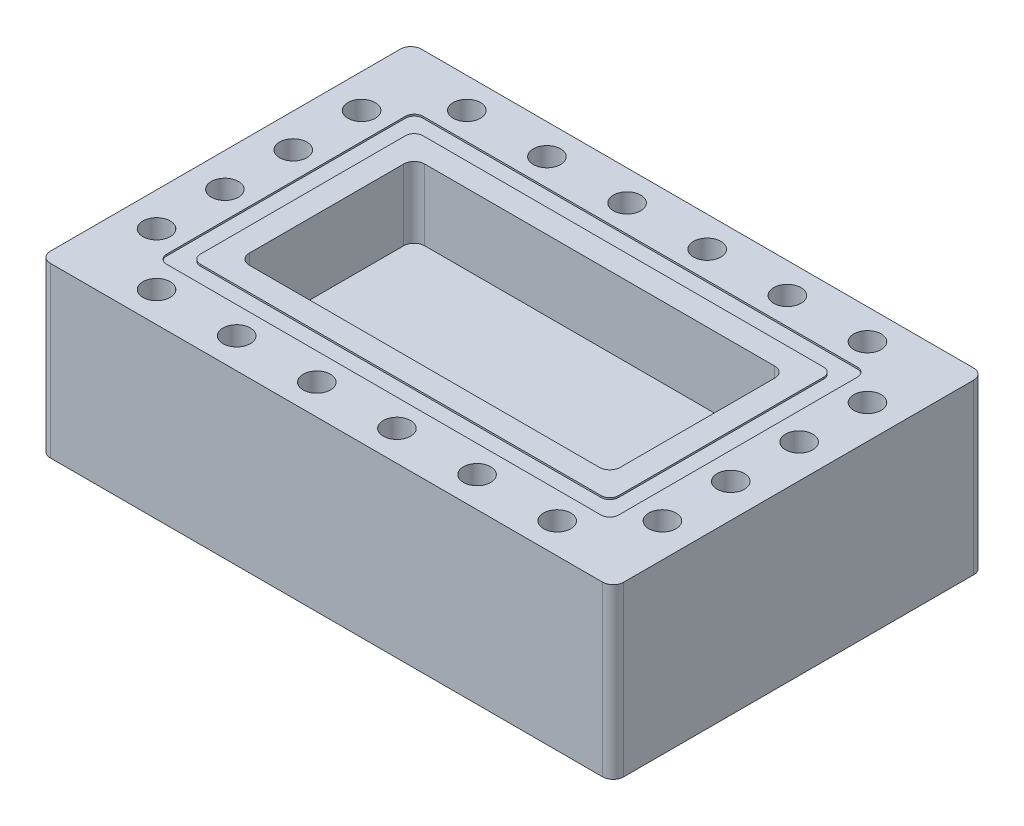
SolidWorks part; units mm, degrees
ref_plane "Front Plane" through (0, 0, 0) normal (0, 0, 1) x (1, 0, 0)
ref_plane "Top Plane" through (0, 0, 0) normal (0, 1, 0) x (1, 0, 0)
ref_plane "Right Plane" through (0, 0, 0) normal (1, 0, 0) x (0, 0, -1)
sketch "Sketch1" plane through (0, 0, 0) normal (0, 1, 0) x (1, 0, 0)
  line L1 (0, 0) -> (85, 0)
  line L2 (0, 0) -> (0, 55)
  line L3 (0, 55) -> (85, 55)
  line L4 (85, 0) -> (85, 55)
  dimension "D1" = 85
  dimension "D2" = 55
extrude "Boss-Extrude1" add sketch "Sketch1" along normal blind 25
sketch "Sketch2" plane through (0, 25, 0) normal (0, 1, 0) x (1, 0, 0)
  line L0 (42.5, 14.5) -> (42.5, 0) construction
  line L1 (15, 40.5) -> (70, 40.5)
  line L2 (15, 40.5) -> (15, 14.5)
  line L3 (15, 14.5) -> (70, 14.5)
  line L4 (70, 40.5) -> (70, 14.5)
  line L5 (0, 0) -> (85, 0) construction
  line L6 (70, 27.5) -> (85, 27.5) construction
  line L7 (85, 0) -> (85, 55) construction
  line L8 (15, 27.5) -> (0, 27.5) construction
  line L9 (0, 55) -> (0, 0) construction
  line L10 (42.5, 40.5) -> (42.5, 55) construction
  line L11 (85, 55) -> (0, 55) construction
  dimension "D1" = 26
  dimension "D2" = 55
extrude "Cut-Extrude1" cut sketch "Sketch2" against normal blind 10.5
fillet "Fillet1" radius 1.55 8 edges at (85, 12.5, -55) (15, 19.75, -40.5) (15, 19.75, -14.5) (70, 19.75, -14.5) (70, 19.75, -40.5) (0, 12.5, -55) (85, 12.5, 0) (0, 12.5, 0)
sketch "Sketch3" plane through (0, 25, 0) normal (0, 1, 0) x (1, 0, 0)
  line L0 (42.5, 14.5) -> (42.5, 11) construction
  line L1 (11.5, 44) -> (73.5, 44)
  line L2 (11.5, 44) -> (11.5, 11)
  line L3 (11.5, 11) -> (73.5, 11)
  line L4 (73.5, 44) -> (73.5, 11)
  line L5 (9, 46.5) -> (76, 46.5)
  line L6 (9, 46.5) -> (9, 8.5)
  line L7 (9, 8.5) -> (76, 8.5)
  line L8 (76, 46.5) -> (76, 8.5)
  line L9 (16.55, 14.5) -> (68.45, 14.5) construction
  line L10 (42.5, 11) -> (42.5, 8.5) construction
  line L11 (42.5, 40.5) -> (42.5, 44) construction
  line L12 (68.45, 40.5) -> (16.55, 40.5) construction
  line L13 (42.5, 44) -> (42.5, 46.5) construction
  line L14 (70, 27.5) -> (73.5, 27.5) construction
  line L15 (70, 16.05) -> (70, 38.95) construction
  line L16 (73.5, 27.5) -> (76, 27.5) construction
  line L17 (15, 27.5) -> (11.5, 27.5) construction
  line L18 (15, 38.95) -> (15, 16.05) construction
  line L19 (11.5, 27.5) -> (9, 27.5) construction
  dimension "D1" = 2.5
  dimension "D2" = 3.5
extrude "Cut-Extrude2" cut sketch "Sketch3" against normal blind 0.25
fillet "Fillet2" radius 1.3 8 edges at (76, 24.875, -46.5) (73.5, 24.875, -44) (73.5, 24.875, -11) (76, 24.875, -8.5) (11.5, 24.875, -11) (9, 24.875, -8.5) (11.5, 24.875, -44) (9, 24.875, -46.5)
sketch "Sketch5" plane through (0, 25, 0) normal (0, 1, 0) x (1, 0, 0)
  line L0 (12.8, 50.5) -> (5, 42.7) construction
  line L1 (5, 42.7) -> (5, 32.5667) construction
  line L2 (5, 32.5667) -> (5, 22.4333) construction
  line L3 (5, 22.4333) -> (5, 12.3) construction
  line L4 (5, 12.3) -> (12.8, 4.5) construction
  line L5 (12.8, 4.5) -> (24.68, 4.5) construction
  line L7 (24.68, 4.5) -> (36.56, 4.5) construction
  line L8 (36.56, 4.5) -> (48.44, 4.5) construction
  line L9 (48.44, 4.5) -> (60.32, 4.5) construction
  line L10 (60.32, 4.5) -> (72.2, 4.5) construction
  line L11 (72.2, 4.5) -> (80, 12.3) construction
  line L12 (80, 12.3) -> (80, 22.4333) construction
  line L13 (80, 22.4333) -> (80, 32.5667) construction
  line L14 (80, 32.5667) -> (80, 42.7) construction
  line L15 (80, 42.7) -> (72.2, 50.5) construction
  line L16 (72.2, 50.5) -> (60.32, 50.5) construction
  line L17 (60.32, 50.5) -> (48.44, 50.5) construction
  line L18 (48.44, 50.5) -> (36.56, 50.5) construction
  line L19 (36.56, 50.5) -> (24.68, 50.5) construction
  line L20 (24.68, 50.5) -> (12.8, 50.5) construction
  line L21 (42.5, 8.5) -> (42.5, 4.5) construction
  line L24 (10.3, 8.5) -> (74.7, 8.5) construction
  line L25 (42.5, 50.5) -> (42.5, 46.5) construction
  line L26 (74.7, 46.5) -> (10.3, 46.5) construction
  line L27 (5, 27.5) -> (9, 27.5) construction
  line L28 (9, 45.2) -> (9, 9.8) construction
  line L29 (76, 27.5) -> (80, 27.5) construction
  line L30 (76, 9.8) -> (76, 45.2) construction
  line L31 (12.8, 11) -> (12.8, 4.5) construction
  line L32 (11.5, 12.3) -> (5, 12.3) construction
  circle A0 centre (5, 42.7) radius 2.025
  circle A1 centre (5, 12.3) radius 2.025
  circle A2 centre (12.8, 4.5) radius 2.025
  circle A3 centre (72.2, 4.5) radius 2.025
  circle A5 centre (24.68, 4.5) radius 2.025
  circle A6 centre (36.56, 4.5) radius 2.025
  circle A7 centre (48.44, 4.5) radius 2.025
  circle A8 centre (60.32, 4.5) radius 2.025
  circle A9 centre (5, 32.5667) radius 2.025
  circle A10 centre (5, 22.4333) radius 2.025
  circle A11 centre (80, 42.7) radius 2.025
  circle A12 centre (80, 12.3) radius 2.025
  circle A13 centre (80, 22.4333) radius 2.025
  circle A14 centre (80, 32.5667) radius 2.025
  circle A15 centre (12.8, 50.5) radius 2.025
  circle A16 centre (24.68, 50.5) radius 2.025
  circle A17 centre (36.56, 50.5) radius 2.025
  circle A18 centre (48.44, 50.5) radius 2.025
  circle A19 centre (60.32, 50.5) radius 2.025
  circle A20 centre (72.2, 50.5) radius 2.025
  dimension "D2" = 4.05
  dimension "D1" = 4
extrude "Cut-Extrude4" cut sketch "Sketch5" against normal through all
